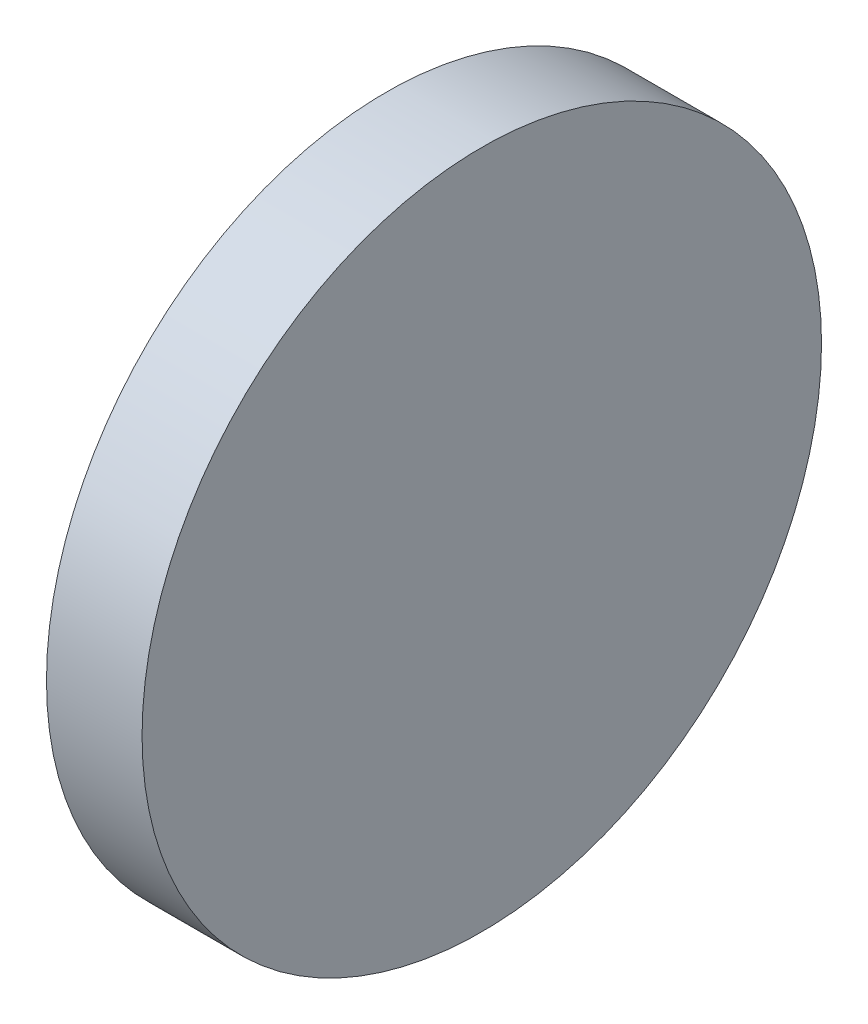
SolidWorks part; units mm, degrees
material "Verre"
ref_plane "Plan de face" through (0, 0, 0) normal (0, 0, 1) x (1, 0, 0)
ref_plane "Plan de dessus" through (0, 0, 0) normal (0, 1, 0) x (1, 0, 0)
ref_plane "Plan de droite" through (0, 0, 0) normal (1, 0, 0) x (0, 0, -1)
sketch "Esquisse1" plane through (0, 0, 0) normal (0, 0, 1) x (1, 0, 0)
  line L1 (-1.055, 0) -> (1.055, 0)
  line L2 (-1.055, 0) -> (-1.055, 7.5)
  line L3 (-1.055, 7.5) -> (1.055, 7.5)
  line L4 (1.055, 0) -> (1.055, 7.5)
revolve "Révolution1" add sketch "Esquisse1" angle 360 about L1
